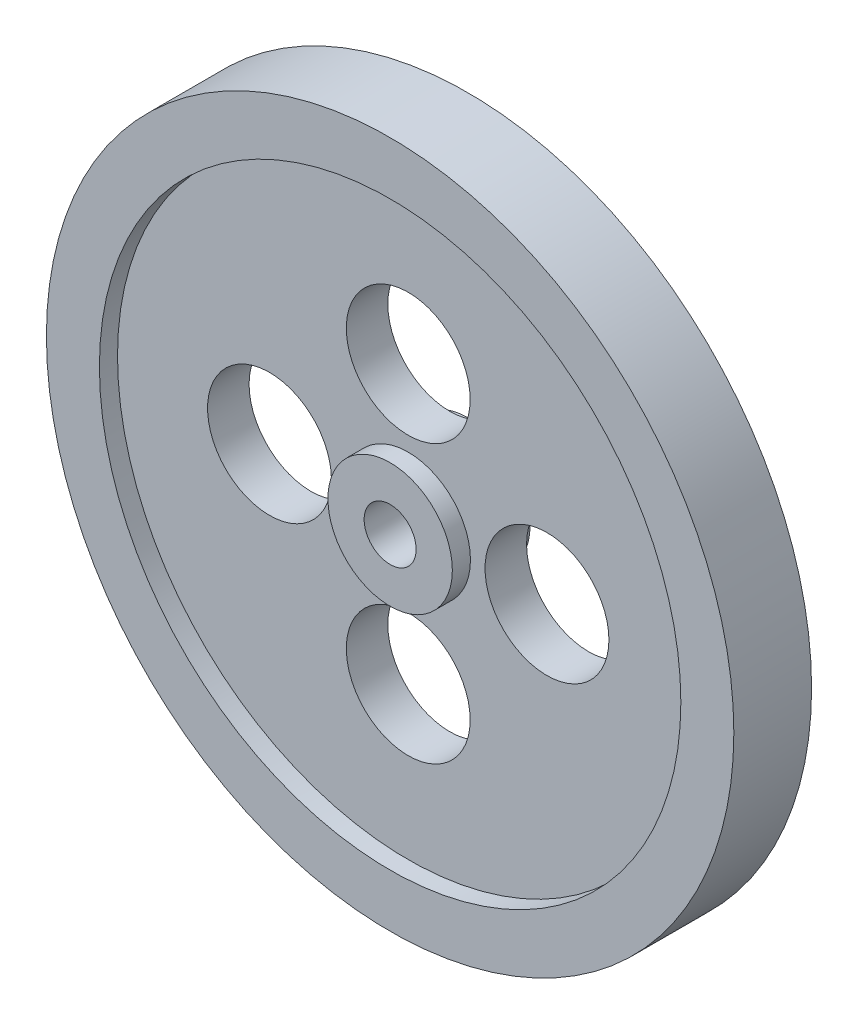
SolidWorks part; units mm, degrees
ref_plane "Front Plane" through (0, 0, 0) normal (0, 0, 1) x (1, 0, 0)
ref_plane "Top Plane" through (0, 0, 0) normal (0, 1, 0) x (1, 0, 0)
ref_plane "Right Plane" through (0, 0, 0) normal (1, 0, 0) x (0, 0, -1)
sketch "Sketch1" plane through (0, 0, 0) normal (0, 0, 1) x (1, 0, 0)
  circle A0 centre (0, 0) radius 24.6683
  circle A1 centre (0, 0) radius 1.8669
  dimension "D1" = 49.3365
  dimension "D2" = 3.7338
extrude "Boss-Extrude1" add sketch "Sketch1" along normal mid plane 5.58
sketch "Sketch2" plane through (0, 0, 2.79) normal (0, 0, 1) x (1, 0, 0)
  circle A0 centre (0, 0) radius 20.865
  circle A1 centre (0, 0) radius 4.465
  dimension "D1" = 41.73
  dimension "D2" = 8.93
extrude "Cut-Extrude1" cut sketch "Sketch2" against normal blind 1.3
sketch "Sketch3" plane through (0, 0, 1.49) normal (0, 0, 1) x (1, 0, 0)
  circle A0 centre (0, 9.9568) radius 4.445
  circle A1 centre (9.9568, 0) radius 4.445
  circle A3 centre (0, -9.9568) radius 4.445
  circle A4 centre (-9.9568, 0) radius 4.445
  point P2 (0, 0)
  point P13 (0, 0)
  dimension "D1" = 28.8036
  dimension "D2" = 8.89
  dimension "D3" = 4
extrude "Cut-Extrude2" cut sketch "Sketch3" against normal through all
mirror "Mirror1" about plane through (0, 0, 0) normal (0, 0, 1) of "Cut-Extrude1"
